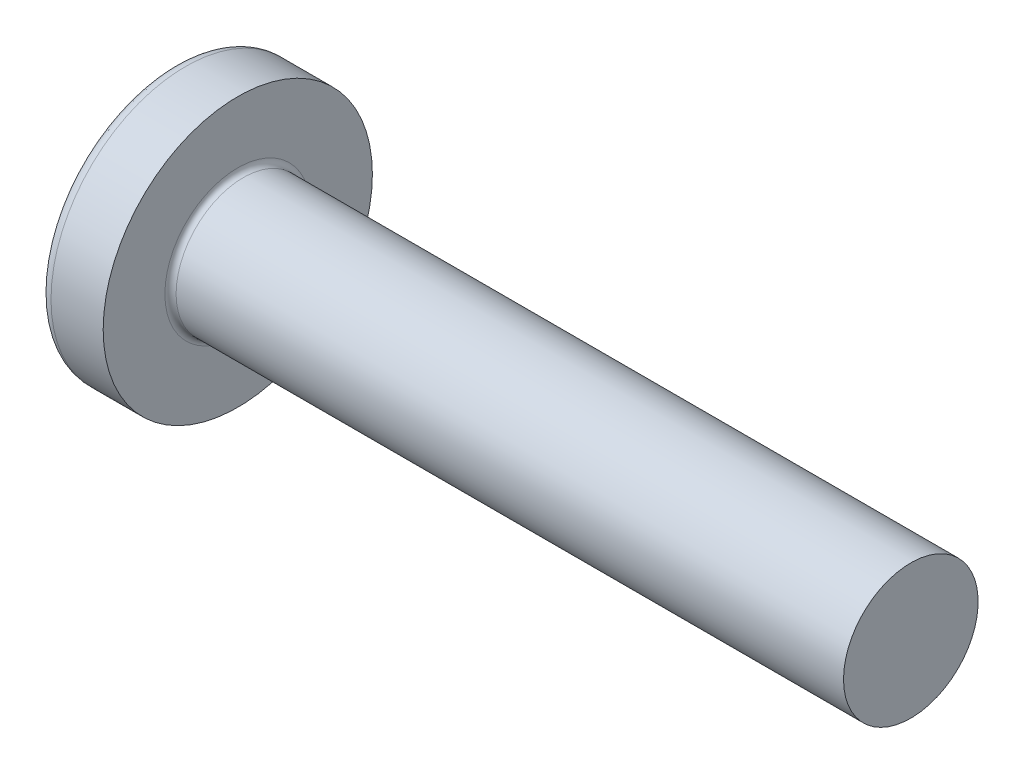
SolidWorks part; units mm, degrees
ref_plane "Plane1" through (0, 0, 0) normal (0, 0, 1) x (1, 0, 0)
ref_plane "Plane2" through (0, 0, 0) normal (0, 1, 0) x (1, 0, 0)
ref_plane "Plane3" through (0, 0, 0) normal (1, 0, 0) x (0, 0, -1)
sketch "BodySke" plane through (0, 0, 0) normal (0, 0, 1) x (1, 0, 0)
  line L0 (4.6, 3) -> (4.6, 6)
  line L1 (5.1, 6.35) -> (5.1, -3.175) construction
  line L2 (-25.4, 0) -> (127, 0) construction
  line L3 (34.6, 0) -> (0, 0)
  line L4 (4.6, 3) -> (34.6, 3)
  line L5 (34.6, 3) -> (34.6, 0)
  line L6 (2.2747, 6) -> (4.6, 6)
  line L8 (4.6, 6.35) -> (4.6, -3.175) construction
  arc A0 (1.8337, 5.7717) -> (0, 0) centre (10, 0) ccw
  arc A2 (1.8337, 5.7717) -> (2.2747, 6) centre (2.2747, 5.46) cw
  dimension "Head_crown_rad" = 10
  dimension "Head_fillet_rad" = 0.54
  dimension "Length" = 30
  dimension "Head_ht" = 4.6
  dimension "Head_dia" = 12
  dimension "Advance" = 1
  dimension "Thread_nom" = 30
  dimension "Diameter" = 6
revolve "Base-Revolve" add sketch "BodySke"
cosmetic thread "ThreadCosmetic" [suppressed]
fillet "Fillet1" radius 0.25 1 edges at (4.6, 0, 3)
sketch "Sketch3" plane through (0, 0, 0) normal (1, 0, 0) x (0, 0, -1)
  line L0 (0.71, -3.35) -> (-0.71, -3.35)
  line L1 (0.71, -3.35) -> (0.71, 3.35)
  line L2 (-0.71, 3.35) -> (0.71, 3.35)
  line L3 (-0.71, 3.35) -> (-0.71, -3.35)
  dimension "Cross_dia" = 6.7
  dimension "D1" = 3.35
  dimension "Cross_width" = 1.42
  dimension "D2" = 0.71
ref_plane "Plane4" through (3.46, 0, 0) normal (1, 0, 0) x (0, 0, -1)
sketch "Sketch4" plane through (3.46, 0, 0) normal (1, 0, 0) x (0, 0, -1)
  line L0 (0.71, -1.6249) -> (-0.71, -1.6249)
  line L1 (0.71, -1.6249) -> (0.71, 1.6249)
  line L2 (-0.71, 1.6249) -> (0.71, 1.6249)
  line L3 (-0.71, 1.6249) -> (-0.71, -1.6249)
  dimension "D1" = 1.42
  dimension "D2" = 3.2498
  dimension "D3" = 0.71
  dimension "D4" = 1.6249
loft "Recess" cut profiles "Sketch3", "Sketch4"
pattern_circular "RecPat" count 2 every 90 about axis through (0, 0, 0) along (1, 0, 0) of "Recess"
sketch "RecCorSke" plane through (0, 0, 0) normal (0, 0, 1) x (1, 0, 0)
  line L0 (-3.175, 0) -> (15.875, 0) construction
  line L1 (-25.4, 0) -> (127, 0) construction
  line L2 (0, 0) -> (0, 1.5224)
  line L3 (0, 1.5224) -> (3.46, 1.2805)
  line L4 (3.46, 1.2805) -> (3.8761, 0)
  line L5 (3.8761, 0) -> (0, 0)
  dimension "Diameter" = 2.561
  dimension "Depth" = 3.46
  dimension "Draft_angle" = 4
  dimension "Bottom_angle" = 18
revolve "RecessCore" cut sketch "RecCorSke" angle 360 about L0
sketch "ThdSchSke" plane through (0, 0, 0) normal (0, 0, 1) x (1, 0, 0)
  line L0 (6.6, -2.4455) -> (6.2117, -3)
  line L1 (6.6, -2.4455) -> (6.9883, -3)
  line L2 (6.9883, -3) -> (6.9883, -3.75)
  line L3 (-3.175, 0) -> (5.1513, 0) construction
  line L5 (6.9883, -3.75) -> (6.2117, -3.75)
  line L6 (6.2117, -3.75) -> (6.2117, -3)
  dimension "Diameter" = 6
  dimension "SideAngle" = 55
  dimension "VeeAngle" = 70
  dimension "Thread_minor" = 4.891
  dimension "Overcut" = 7.5
  dimension "Start" = 6.6
revolve "ThreadSchematic" [suppressed] cut sketch "ThdSchSke" angle 360 about L3
pattern_linear "ThdSchPat" [suppressed]
equation "\"D1@Sketch3\" = \"Cross_dia@Sketch3\" / 2"
equation "\"D2@Sketch3\" = \"Cross_width@Sketch3\" / 2"
equation "\"Depth@RecCorSke\" = \"Cross_depth@Plane4\""
equation "\"D1@Sketch4\" = \"Cross_width@Sketch3\""
equation "\"D2@Sketch4\" = \"Cross_dia@Sketch3\" - 2.0 * \"Cross_depth@Plane4\" * tan(26.5  * 0.017453292)"
equation "\"D3@Sketch4\" = \"D1@Sketch4\" / 2"
equation "\"D4@Sketch4\" = \"D2@Sketch4\" / 2"
equation "\"Thread_length@ThreadCosmetic\" = ((sgn( (\"Length@BodySke\" - \"Advance@BodySke\" * 2.0 ) - \"Thread_nom@BodySke\" )-1)*( (\"Length@BodySke\" - \"Advance@BodySke\" * 2.0 ) - \"Thread_nom@BodySke\" ))/-2+ \"Thread_nom@BodySke\""
equation "\"Thread_minor@ThdSchSke\" = \"Thread_minor@ThreadCosmetic\""
equation "\"Diameter@ThdSchSke\" = \"Diameter@BodySke\""
equation "\"Overcut@ThdSchSke\" = \"Diameter@BodySke\" * 1.25"
equation "\"Start@ThdSchSke\" = \"Head_ht@BodySke\" + \"Length@BodySke\" - \"Thread_length@ThreadCosmetic\"  '---Non-countersunk---"
equation "\"Num_threads@ThdSchPat\" = int( \"Thread_length@ThreadCosmetic\" / \"Advance@BodySke\" + 0.999 )  + 1"
equation "\"Advance@ThdSchPat\" = \"Thread_length@ThreadCosmetic\" /  (\"Num_threads@ThdSchPat\" - 1) 'relax it"
